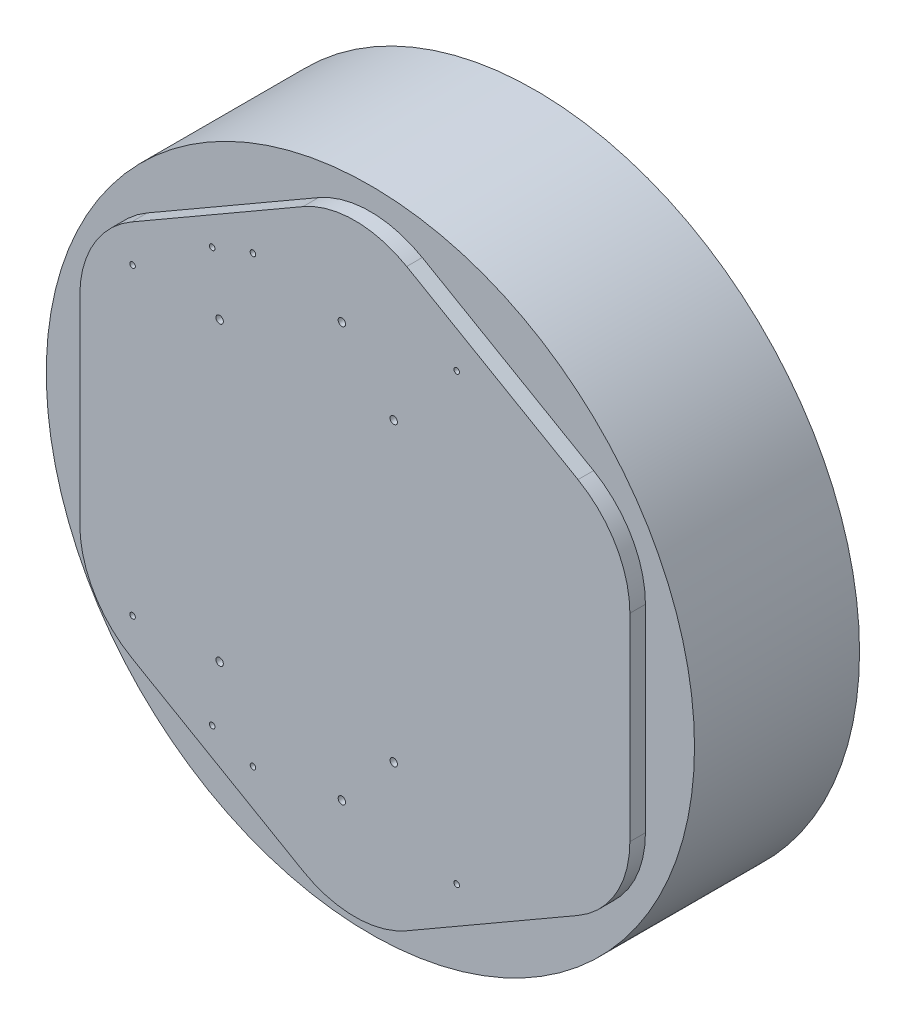
SolidWorks part; units mm, degrees
ref_plane "Plano frontal" through (0, 0, 0) normal (0, 0, 1) x (1, 0, 0)
ref_plane "Plano superior" through (0, 0, 0) normal (0, 1, 0) x (1, 0, 0)
ref_plane "Plano direito" through (0, 0, 0) normal (1, 0, 0) x (0, 0, -1)
sketch "Esboço1" plane through (0, 0, 0) normal (0, 0, 1) x (1, 0, 0)
  circle A0 centre (0, 0) radius 175
extrude "Ressalto-extrusão1" add sketch "Esboço1" along normal blind 97.5
sketch "Esboço4" plane through (0, 0, 97.5) normal (0, 0, 1) x (1, 0, 0)
  line L0 (0, 0) -> (-7, 0) construction
  line L1 (0, 0) -> (-55, 0) construction
  line L2 (0, 0) -> (-73, 0) construction
  line L3 (0, 0) -> (-77, 0) construction
  line L4 (0, 0) -> (-120, 0) construction
  line L5 (0, 0) -> (21, 0) construction
  line L6 (0, 0) -> (55, 0) construction
  line L14 (-202, 0) -> (175, 0) construction
  circle A0 centre (-120, 82) radius 1.5
  circle A1 centre (-55, 120) radius 1.5
  circle A2 centre (-77, 111.8) radius 1.5
  circle A3 centre (55, 120) radius 1.5
  circle A4 centre (-7, 111.8) radius 2
  circle A5 centre (-73, 80) radius 2
  circle A6 centre (21, 80) radius 2
  arc A7 (-38, 0) -> (-202, 0) centre (-120, 0) ccw construction
  arc A8 (7, 0) -> (-153, 0) centre (-73, 0) ccw construction
  arc A9 (34.8, 0) -> (-188.8, 0) centre (-77, 0) ccw construction
  arc A10 (65, 0) -> (-175, 0) centre (-55, 0) ccw construction
  arc A11 (101, 0) -> (-59, 0) centre (21, 0) ccw construction
  arc A12 (104.8, 0) -> (-118.8, 0) centre (-7, 0) ccw construction
  arc A13 (175, 0) -> (-65, 0) centre (55, 0) ccw construction
  circle A14 centre (21, -80) radius 2
  circle A15 centre (-73, -80) radius 2
  circle A16 centre (-7, -111.8) radius 2
  circle A17 centre (55, -120) radius 1.5
  circle A18 centre (-77, -111.8) radius 1.5
  circle A19 centre (-55, -120) radius 1.5
  circle A20 centre (-120, -82) radius 1.5
extrude "Corte-extrusão1" cut sketch "Esboço4" against normal blind 10
sketch "Esboço5" plane through (0, 0, 97.5) normal (0, 0, 1) x (1, 0, 0)
  line L1 (28, -155.3072) -> (120.5, -101.9023)
  line L2 (148.5, -53.4049) -> (148.5, 53.4049)
  line L3 (120.5, 101.9023) -> (28, 155.3072)
  line L4 (-28, 155.3072) -> (-120.5, 101.9023)
  line L5 (-148.5, 53.4049) -> (-148.5, -53.4049)
  line L6 (-120.5, -101.9023) -> (-28, -155.3072)
  circle A0 centre (0, 0) radius 148.5 construction
  arc A1 (28, 155.3072) -> (-28, 155.3072) centre (0, 106.8098) ccw
  arc A2 (148.5, 53.4049) -> (120.5, 101.9023) centre (92.5, 53.4049) ccw
  arc A3 (120.5, -101.9023) -> (148.5, -53.4049) centre (92.5, -53.4049) ccw
  arc A4 (28, -155.3072) -> (-28, -155.3072) centre (0, -106.8098) cw
  arc A5 (-148.5, -53.4049) -> (-120.5, -101.9023) centre (-92.5, -53.4049) ccw
  arc A6 (-120.5, 101.9023) -> (-148.5, 53.4049) centre (-92.5, 53.4049) ccw
  dimension "D1" = 56
extrude "Corte-extrusão2" cut sketch "Esboço5" against normal blind 8.4 flip side to cut
